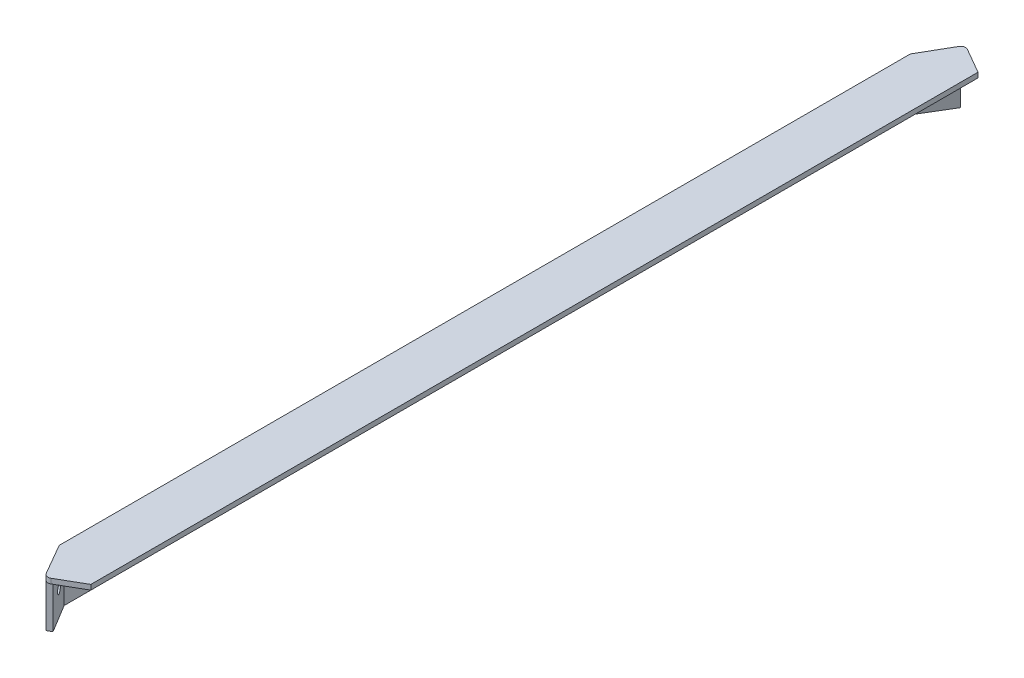
SolidWorks part; units mm, degrees
ref_plane "Front Plane" through (0, 0, 0) normal (0, 0, 1) x (1, 0, 0)
ref_plane "Top Plane" through (0, 0, 0) normal (0, 1, 0) x (1, 0, 0)
ref_plane "Right Plane" through (0, 0, 0) normal (1, 0, 0) x (0, 0, -1)
sketch "Sketch1" plane through (0, 0, 0) normal (0, 0, 1) x (1, 0, 0)
  line L6 (0, 0) -> (0, 70)
  line L7 (0, 70) -> (70, 70)
  line L8 (70, 70) -> (70, 63)
  line L9 (70, 63) -> (7, 63)
  line L10 (7, 63) -> (7, 0)
  line L11 (7, 0) -> (0, 0)
  dimension "D1" = 70
  dimension "D2" = 70
  dimension "D3" = 7
  dimension "D4" = 7
extrude "Boss-Extrude1" add sketch "Sketch1" along normal blind 600
sketch "Sketch2" plane through (0, 0, 0) normal (0, 1, 0) x (1, 0, 0)
  line L0 (0, -600) -> (25, -643.3013)
  line L1 (25, -643.3013) -> (31.0622, -639.8013)
  line L2 (31.0622, -639.8013) -> (7, -600)
  line L3 (0, -600) -> (7, -600) construction
  line L4 (7, -600) -> (0, -600)
  line L5 (0, -600) -> (0, 0) construction
  dimension "D1" = 46.5095
  dimension "D2" = 50
  dimension "D3" = 210
  dimension "D4" = 7
extrude "Boss-Extrude2" add sketch "Sketch2" along normal blind 63
sketch "Sketch9" plane through (0, 63, 0) normal (0, 1, 0) x (1, 0, 0)
  line L0 (0, -600) -> (25, -643.3013)
  line L1 (34.5622, -645.8634) -> (70, -625.4034)
  line L2 (70, -625.4034) -> (70, -600)
  line L3 (70, -600) -> (0, -600)
  arc A0 (25, -643.3013) -> (34.5622, -645.8634) centre (31.0622, -639.8013) ccw
  dimension "D5" = 14
  dimension "D2" = 40.9201
  dimension "D1" = 90
  dimension "D3" = 90
  dimension "D4" = 60
  dimension "D6" = 7
  dimension "D7" = 7
extrude "Boss-Extrude4" add sketch "Sketch9" along normal blind 7
sketch "Sketch10" plane through (-260.518, 0, 157.4982) normal (0.8558, 0, -0.5174) x (-0.5174, 0, -0.8558)
  line L0 (-563.5913, 63) -> (-563.5913, 0) construction
  line L1 (-563.5913, 0) -> (-517.0819, 0) construction
  circle A0 centre (-538.5913, 35) radius 6
  dimension "D1" = 12
  dimension "D2" = 25
  dimension "D3" = 35
extrude "Cut-Extrude3" cut sketch "Sketch10" against normal blind 7
sketch "Sketch21" plane through (0, 0, 0) normal (0, 0, -1) x (-1, 0, 0)
  line L0 (0, 70) -> (-70, 70) construction
  line L1 (-70, 70) -> (-70, 0) construction
  line L2 (-70, 0) -> (0, 0) construction
  line L3 (0, 0) -> (0, 69.2595) construction
fillet "Fillet5" radius 5 2 edges at (19.0311, 63, 619.9006) (7, 63, 300)
mirror "Mirror6" about plane through (0, 0, 0) normal (0, 0, 1) of bodies 107 108
